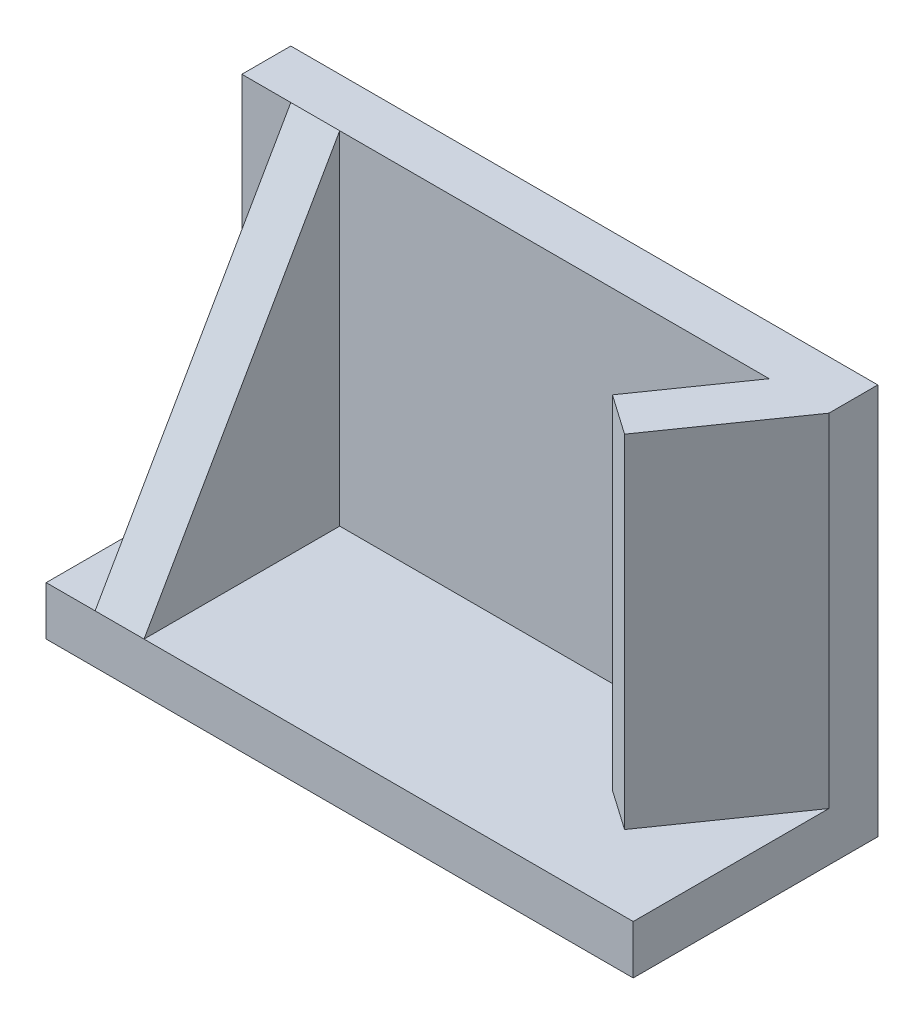
SolidWorks part; units mm, degrees
ref_plane "前基準面" through (0, 0, 0) normal (0, 0, 1) x (1, 0, 0)
ref_plane "上基準面" through (0, 0, 0) normal (0, 1, 0) x (1, 0, 0)
ref_plane "右基準面" through (0, 0, 0) normal (1, 0, 0) x (0, 0, -1)
sketch "草圖1" plane through (0, 0, 0) normal (1, 0, 0) x (0, 0, -1)
  line L0 (-40, 0) -> (0, 0)
  line L1 (0, 0) -> (0, 70)
  line L2 (0, 70) -> (10, 70)
  line L3 (10, 70) -> (10, -10)
  line L4 (10, -10) -> (-40, -10)
  line L5 (-40, -10) -> (-40, 0)
  dimension "D1" = 10
  dimension "D2" = 80
  dimension "D3" = 50
  dimension "D4" = 10
extrude "填料-伸長1" add sketch "草圖1" along normal blind 120
sketch "草圖2" plane through (0, 70, 0) normal (0, 1, 0) x (1, 0, 0)
  line L0 (120, 0) -> (102.8345, -24.6038)
  line L1 (102.8345, -24.6038) -> (94.6333, -18.882)
  line L2 (94.6333, -18.882) -> (107.8068, 0)
  line L3 (120, 0) -> (0, 0) construction
  line L4 (107.8068, 0) -> (120, 0)
  dimension "D1" = 30
  dimension "D2" = 10
extrude "填料-伸長2" add sketch "草圖2" against normal up to next
ref_plane "平面1" through (10, 0, 0) normal (1, 0, 0) x (0, 0, -1)
sketch "草圖3" plane through (10, 0, 0) normal (1, 0, 0) x (0, 0, -1)
  line L0 (0, 70) -> (0, 0)
  line L4 (0, 0) -> (-40, 0)
  line L5 (-40, 0) -> (0, 70)
extrude "填料-伸長3" add sketch "草圖3" along normal blind 10
